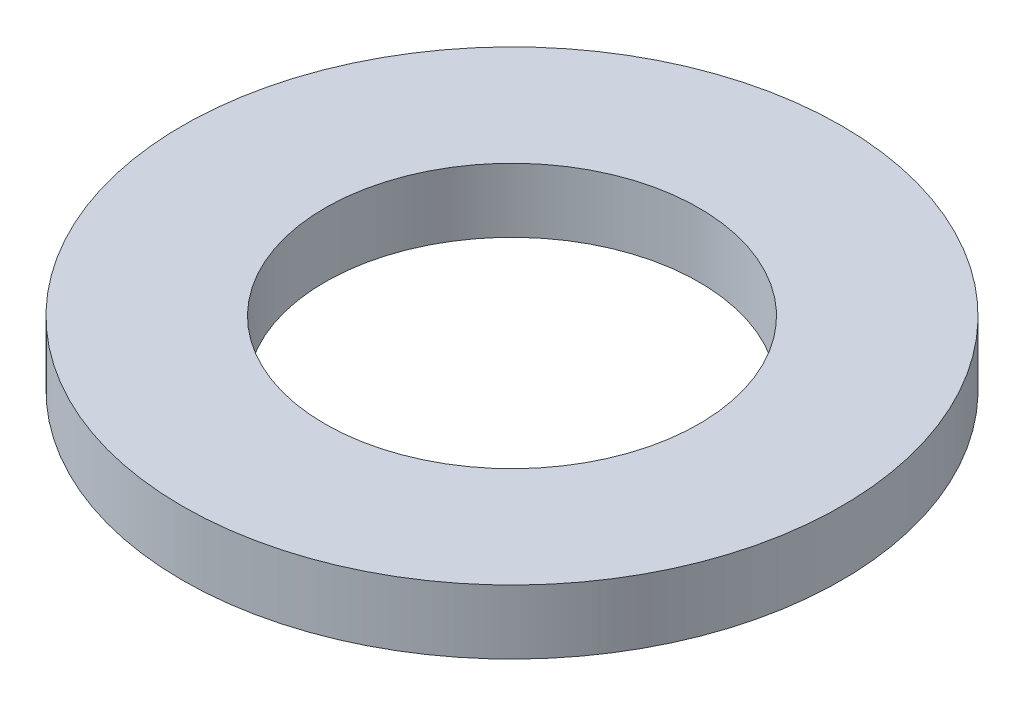
SolidWorks part; units mm, degrees
ref_plane "Front Plane" through (0, 0, 0) normal (0, 0, 1) x (1, 0, 0)
ref_plane "Top Plane" through (0, 0, 0) normal (0, 1, 0) x (1, 0, 0)
ref_plane "Right Plane" through (0, 0, 0) normal (1, 0, 0) x (0, 0, -1)
sketch "Sketch1" plane through (0, 0, 0) normal (0, 1, 0) x (1, 0, 0)
  circle A0 centre (0, 0) radius 61.6585
  circle A1 centre (0, 0) radius 35
  dimension "D1" = 70
extrude "Boss-Extrude1" add sketch "Sketch1" along normal blind 12
